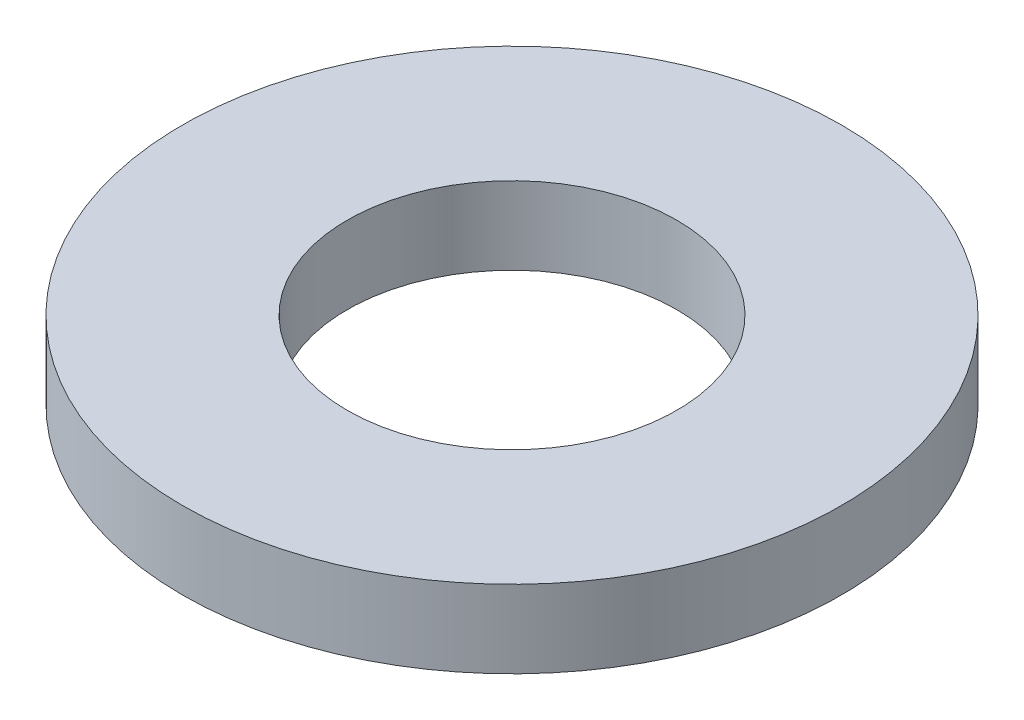
SolidWorks part; units mm, degrees
ref_plane "Front Plane" through (0, 0, 0) normal (0, 0, 1) x (1, 0, 0)
ref_plane "Top Plane" through (0, 0, 0) normal (0, 1, 0) x (1, 0, 0)
ref_plane "Right Plane" through (0, 0, 0) normal (1, 0, 0) x (0, 0, -1)
sketch "Sketch1" plane through (0, 0, 0) normal (0, 1, 0) x (1, 0, 0)
  circle A0 centre (0, 0) radius 4.25
  circle A1 centre (0, 0) radius 8.5
  dimension "D1" = 8.5
  dimension "D2" = 17
extrude "Boss-Extrude1" add sketch "Sketch1" along normal blind 2
